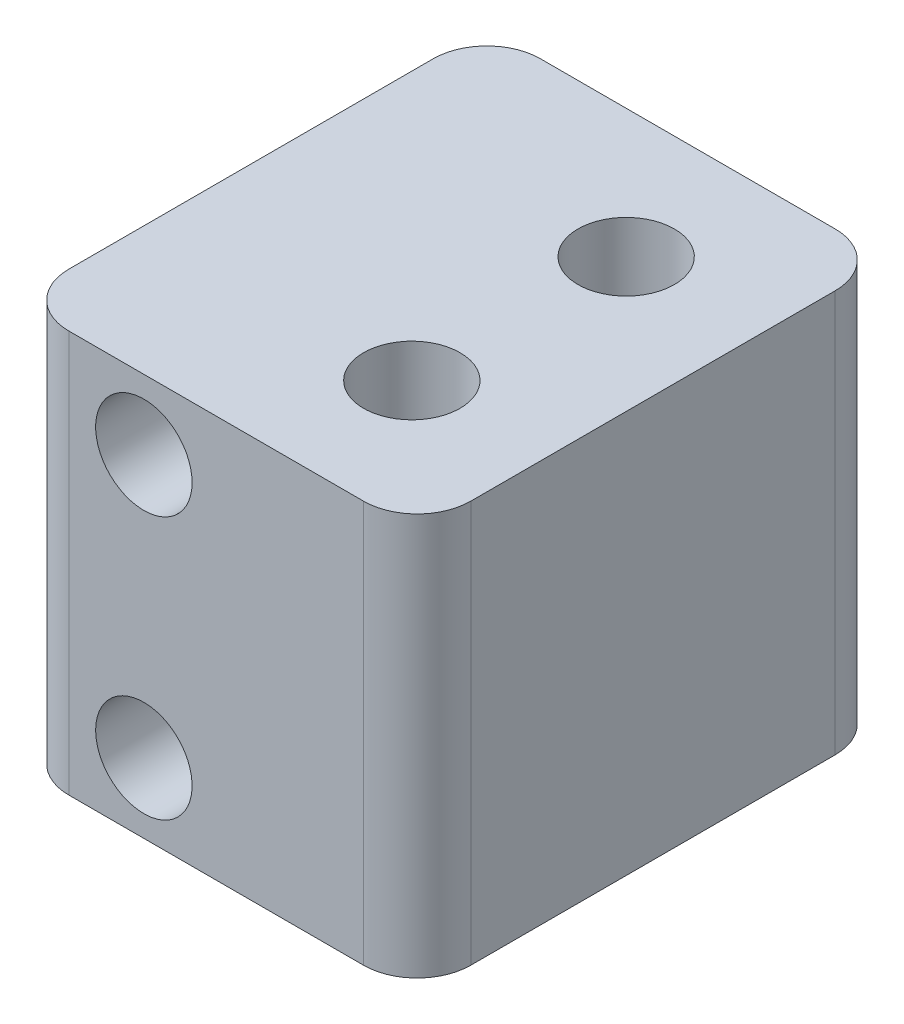
SolidWorks part; units mm, degrees
ref_plane "Front Plane" through (0, 0, 0) normal (0, 0, 1) x (1, 0, 0)
ref_plane "Top Plane" through (0, 0, 0) normal (0, 1, 0) x (1, 0, 0)
ref_plane "Right Plane" through (0, 0, 0) normal (1, 0, 0) x (0, 0, -1)
sketch "Sketch1" plane through (0, 0, 0) normal (0, 1, 0) x (1, 0, 0)
  line L0 (-9.525, 0) -> (9.525, 0) construction
  line L1 (-9.525, 11.176) -> (9.525, 11.176)
  line L2 (-9.525, 11.176) -> (-9.525, -11.176)
  line L3 (-9.525, -11.176) -> (9.525, -11.176)
  line L4 (9.525, 11.176) -> (9.525, -11.176)
  line L5 (-9.525, 11.176) -> (9.525, -11.176) construction
  line L6 (-9.525, -11.176) -> (9.525, 11.176) construction
  circle A0 centre (3.175, 5.08) radius 2.286
  circle A1 centre (3.175, -5.08) radius 2.286
  point P0 (0, 0)
  dimension "D4" = 4.572
  dimension "D1" = 22.352
  dimension "D2" = 19.05
  dimension "D3" = 5.08
  dimension "D5" = 3.175
extrude "Boss-Extrude1" add sketch "Sketch1" along normal blind 19.05
fillet "Fillet1" radius 2.54 2 edges at (9.525, 9.525, -11.176) (9.525, 9.525, 11.176)
fillet "Fillet2" radius 2.54 2 edges at (-9.525, 9.525, 11.176) (-9.525, 9.525, -11.176)
sketch "Sketch2" plane through (0, 0, 11.176) normal (0, 0, 1) x (1, 0, 0)
  line L0 (0, 19.05) -> (0, 0) construction
  line L1 (-6.985, 19.05) -> (6.985, 19.05) construction
  line L2 (0, 9.525) -> (-9.525, 9.525) construction
  line L3 (-9.525, 0) -> (-9.525, 19.05) construction
  circle A0 centre (-3.429, 15.748) radius 2.286
  circle A1 centre (-3.429, 3.302) radius 2.286
  point P7 (0, 9.525)
  dimension "D3" = 4.572
  dimension "D1" = 6.223
  dimension "D2" = 3.429
extrude "Cut-Extrude1" cut sketch "Sketch2" against normal through all
